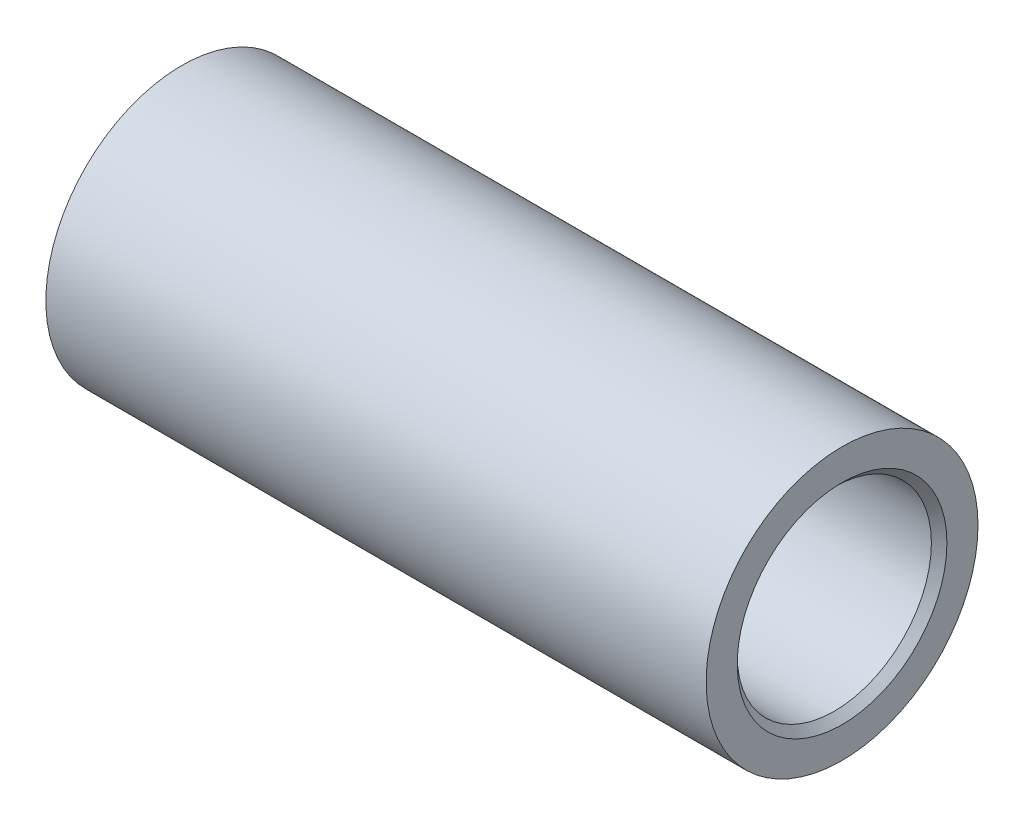
SolidWorks part; units mm, degrees
ref_plane "Płaszczyzna przednia" through (0, 0, 0) normal (0, 0, 1) x (1, 0, 0)
ref_plane "Płaszczyzna górna" through (0, 0, 0) normal (0, 1, 0) x (1, 0, 0)
ref_plane "Płaszczyzna prawa" through (0, 0, 0) normal (1, 0, 0) x (0, 0, -1)
sketch "Szkic1" plane through (0, 0, 0) normal (1, 0, 0) x (0, 0, -1)
  circle A0 centre (0, 0) radius 17.5
  circle A1 centre (0, 0) radius 12.5
  dimension "D1" = 35
  dimension "D2" = 25
extrude "Dodanie-wyciągnięcie1" add sketch "Szkic1" along normal blind 85
chamfer "Sfazowanie1" distance 1 angle 45 2 edges at (0, 0, -12.5) (85, 0, -12.5)
